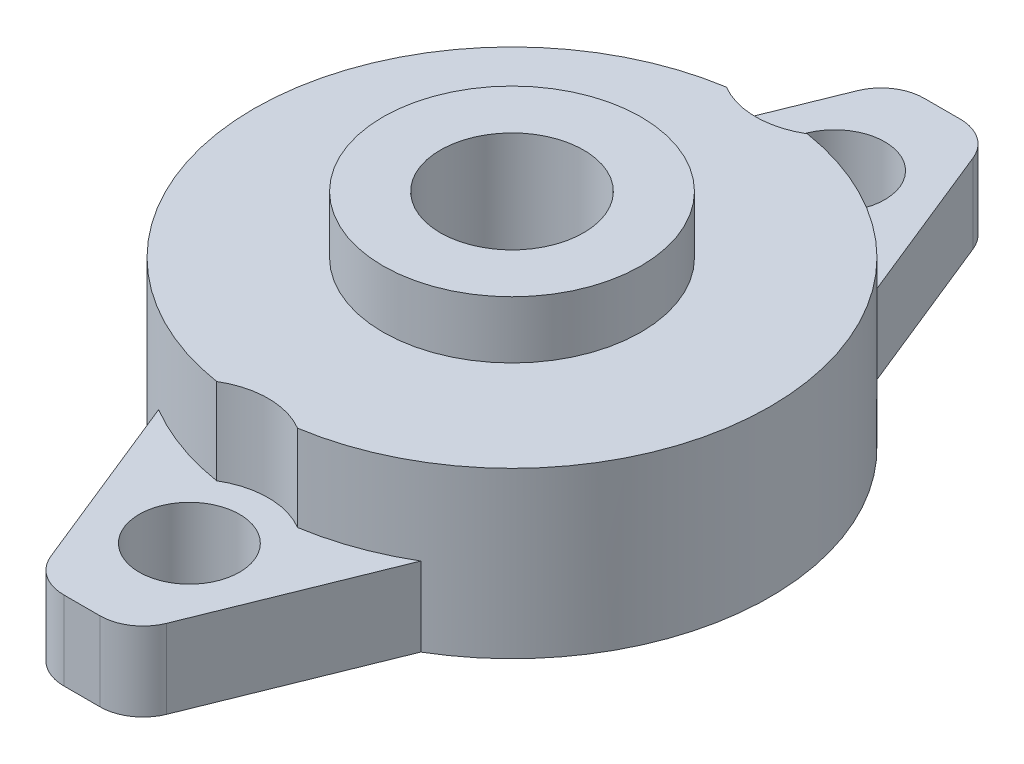
SolidWorks part; units mm, degrees
ref_plane "前视基准面" through (0, 0, 0) normal (0, 0, 1) x (1, 0, 0)
ref_plane "上视基准面" through (0, 0, 0) normal (0, 1, 0) x (1, 0, 0)
ref_plane "右视基准面" through (0, 0, 0) normal (1, 0, 0) x (0, 0, -1)
sketch "Sketch1" plane through (0, 0, 0) normal (0, 1, 0) x (1, 0, 0)
  line L0 (-9.142, 15.5056) -> (-4.044, 28.1238)
  line L1 (4.044, 28.1238) -> (9.142, 15.5056)
  line L2 (-18, 0) -> (18, 0) construction
  line L3 (-9.142, 15.5056) -> (9.142, 15.5056) construction
  line L4 (-1.2624, 30) -> (1.2624, 30)
  line L5 (-1.2624, -30) -> (1.2624, -30)
  line L6 (-9.142, -15.5056) -> (9.142, -15.5056) construction
  line L7 (4.044, -28.1238) -> (9.142, -15.5056)
  line L8 (-9.142, -15.5056) -> (-4.044, -28.1238)
  line L9 (-1.2624, 27) -> (1.2624, -27) construction
  line L10 (0, 22.5) -> (0, -22.5) construction
  arc A0 (-9.142, 15.5056) -> (-9.142, -15.5056) centre (0, 0) ccw
  arc A1 (4.044, -28.1238) -> (1.2624, -30) centre (1.2624, -27) cw
  arc A2 (-4.044, -28.1238) -> (-1.2624, -30) centre (-1.2624, -27) ccw
  arc A3 (1.2624, 30) -> (4.044, 28.1238) centre (1.2624, 27) cw
  arc A4 (-4.044, 28.1238) -> (-1.2624, 30) centre (-1.2624, 27) cw
  circle A5 centre (0, 22.5) radius 3.5
  circle A6 centre (0, -22.5) radius 3.5
  arc A7 (9.142, -15.5056) -> (9.142, 15.5056) centre (0, 0) ccw
  point P15 (3.286, -30)
  point P18 (-3.286, -30)
  point P21 (3.286, 30)
  point P24 (-3.286, 30)
  point P29 (-5.4705, 28.2845)
  point P30 (9.8358, 15.0751)
  point P31 (9.142, 15.5056)
  point P32 (1.2624, 30)
  point P33 (4.8694, 0)
  dimension "D1" = 36
  dimension "D2" = 60
  dimension "D3" = 3
  dimension "D4" = 7
  dimension "D5" = 45
  dimension "D6" = 22.5
extrude "Extrude1" add sketch "Sketch1" along normal blind 5.5
sketch "Sketch2" plane through (0, 5.5, 0) normal (0, 1, 0) x (1, 0, 0)
  arc A0 (2.8197, -17.7778) -> (2.8197, 17.7778) centre (0, 0) ccw
  arc A1 (-2.8197, 17.7778) -> (2.8197, 17.7778) centre (0, 22.5) ccw
  arc A2 (2.8197, -17.7778) -> (-2.8197, -17.7778) centre (0, -22.5) ccw
  arc A3 (-2.8197, 17.7778) -> (-2.8197, -17.7778) centre (0, 0) ccw
  dimension "D1" = 11
extrude "Extrude2" add sketch "Sketch2" along normal blind 6
sketch "Sketch3" plane through (0, 11.5, 0) normal (0, 1, 0) x (1, 0, 0)
  circle A0 centre (0, 0) radius 9
  dimension "D1" = 18
extrude "Extrude3" add sketch "Sketch3" along normal blind 4
sketch "Sketch4" plane through (0, 15.5, 0) normal (0, 1, 0) x (1, 0, 0)
  circle A0 centre (0, 0) radius 5
  dimension "D1" = 10
extrude "Extrude4" cut sketch "Sketch4" against normal blind 20
sketch "Sketch5" plane through (0, 0, 0) normal (0, -1, 0) x (1, 0, 0)
  circle A0 centre (0, 0) radius 14
  dimension "D1" = 28
extrude "Extrude5" cut sketch "Sketch5" against normal blind 1.5
